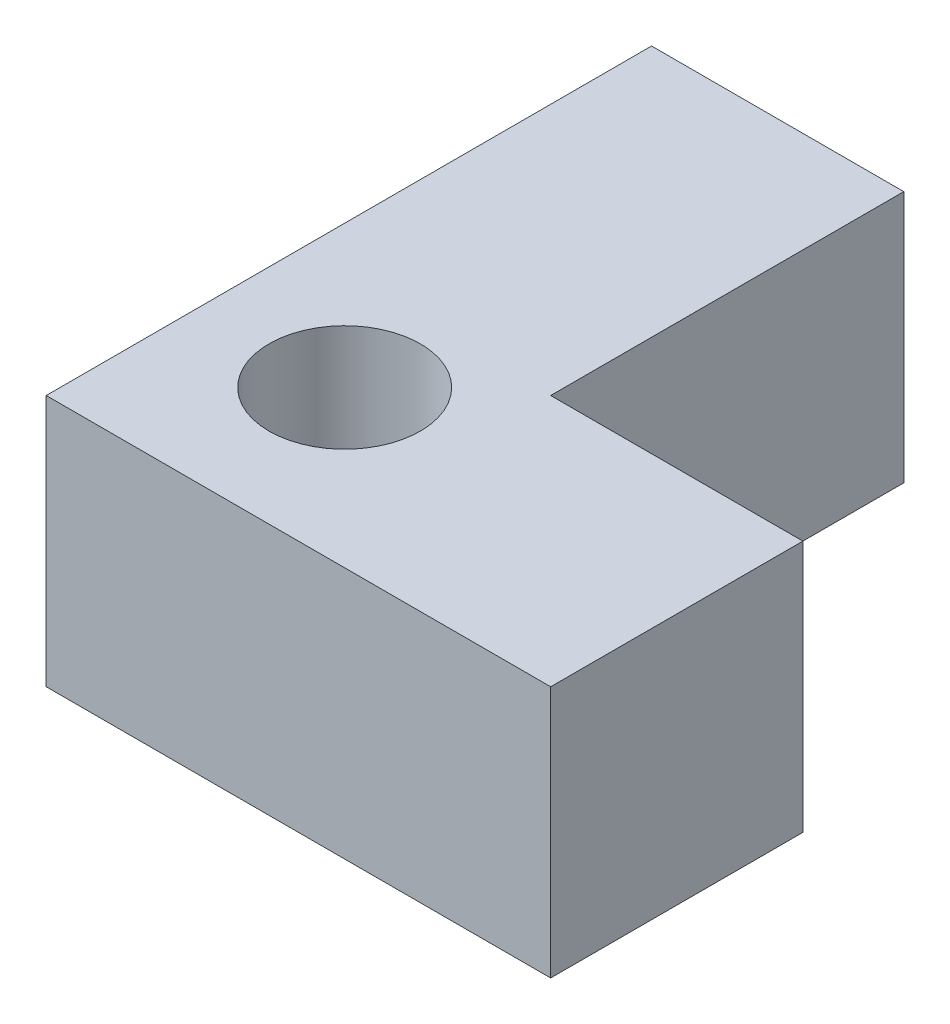
SolidWorks part; units mm, degrees
ref_plane "Front Plane" through (0, 0, 0) normal (0, 0, 1) x (1, 0, 0)
ref_plane "Top Plane" through (0, 0, 0) normal (0, 1, 0) x (1, 0, 0)
ref_plane "Right Plane" through (0, 0, 0) normal (1, 0, 0) x (0, 0, -1)
sketch "Sketch1" plane through (0, 0, 0) normal (0, 1, 0) x (1, 0, 0)
  line L0 (-38.9145, 22.6156) -> (-38.9145, -7.8644)
  line L1 (-38.9145, 22.6156) -> (-26.2145, 22.6156)
  line L2 (-26.2145, 22.6156) -> (-26.2145, 4.8356)
  line L3 (-26.2145, 4.8356) -> (-13.5145, 4.8356)
  line L4 (-13.5145, 4.8356) -> (-13.5145, -7.8644)
  line L5 (-13.5145, -7.8644) -> (-38.9145, -7.8644)
extrude "Boss-Extrude1" add sketch "Sketch1" along normal blind 12.7
sketch "Sketch2" plane through (0, 12.7, 0) normal (0, 1, 0) x (1, 0, 0)
  circle A0 centre (-31.75, 0) radius 3.81
extrude "Cut-Extrude1" cut sketch "Sketch2" against normal through all contours A0
